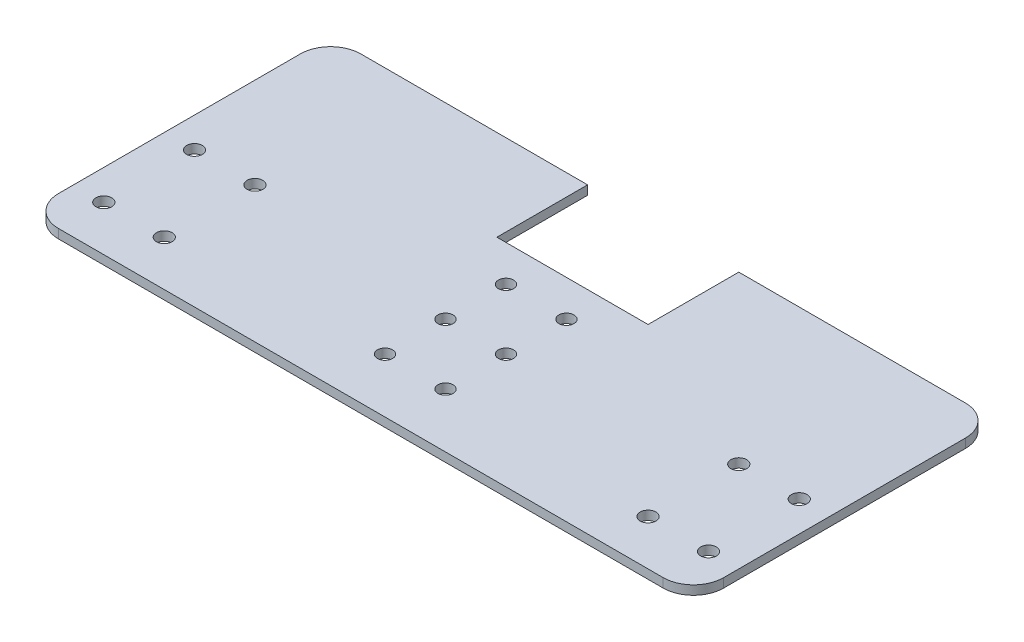
SolidWorks part; units mm, degrees
ref_plane "前视基准面" through (0, 0, 0) normal (0, 0, 1) x (1, 0, 0)
ref_plane "上视基准面" through (0, 0, 0) normal (0, 1, 0) x (1, 0, 0)
ref_plane "右视基准面" through (0, 0, 0) normal (1, 0, 0) x (0, 0, -1)
sketch "草图1" plane through (0, 0, 0) normal (0, 1, 0) x (1, 0, 0)
  line L1 (-100, 50) -> (100, 50)
  line L2 (-110, 40) -> (-110, -40)
  line L3 (-100, -50) -> (100, -50)
  line L4 (110, 40) -> (110, -40)
  line L5 (-110, 50) -> (110, -50) construction
  line L6 (-110, -50) -> (110, 50) construction
  arc A0 (100, 50) -> (110, 40) centre (100, 40) cw
  arc A1 (110, -40) -> (100, -50) centre (100, -40) cw
  arc A2 (-100, -50) -> (-110, -40) centre (-100, -40) cw
  arc A3 (-110, 40) -> (-100, 50) centre (-100, 40) cw
  point P0 (0, 0)
  dimension "D1" = 10
extrude "尾增加底盘" add sketch "草图1" along normal blind 3
sketch "草图2" plane through (0, 3, 0) normal (0, 1, 0) x (1, 0, 0)
  line L0 (100, 50) -> (-100, 50) construction
  line L1 (-25, 50) -> (25, 50)
  line L2 (-25, 50) -> (-25, 20)
  line L3 (-25, 20) -> (25, 20)
  line L4 (25, 50) -> (25, 20)
  point P6 (0, 0)
  point P7 (0, 0)
  point P8 (0, 0)
  point P9 (0, 0)
extrude "切除" cut sketch "草图2" against normal through all
sketch "草图3" plane through (0, 3, 0) normal (0, 1, 0) x (1, 0, 0)
  circle A0 centre (10, 8) radius 2.5
  circle A1 centre (10, -12) radius 2.5
  circle A2 centre (10, -32) radius 2.5
  circle A3 centre (-10, -32) radius 2.5
  circle A4 centre (-10, -12) radius 2.5
  circle A5 centre (-10, 8) radius 2.5
  dimension "D1" = 3
  dimension "D2" = 3
extrude "固定位孔" cut sketch "草图3" against normal through all
sketch "草图4" plane through (0, 3, 0) normal (0, 1, 0) x (1, 0, 0)
  circle A0 centre (100, -35) radius 2.6
  circle A1 centre (80, -35) radius 2.6
  circle A2 centre (100, -5) radius 2.6
  circle A3 centre (80, -5) radius 2.6
  circle A5 centre (-100, -35) radius 2.6
  circle A6 centre (-100, -5) radius 2.6
  circle A7 centre (-80, -35) radius 2.6
  circle A8 centre (-80, -5) radius 2.6
extrude "电机位孔" cut sketch "草图4" against normal through all
